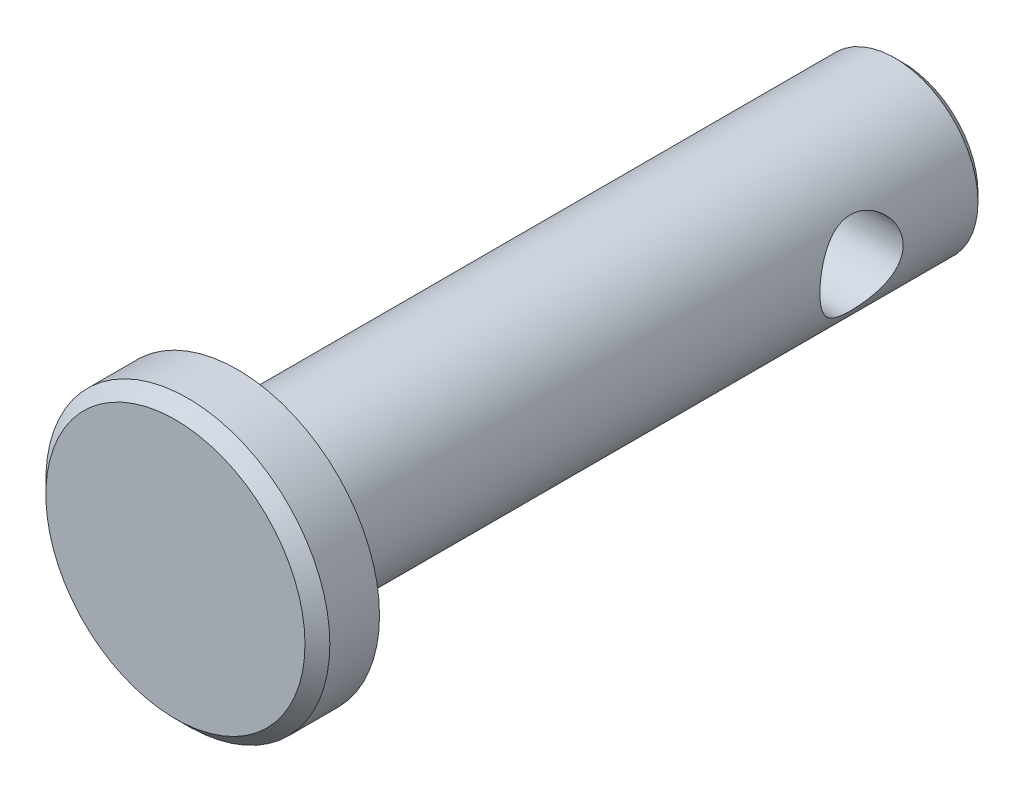
SolidWorks part; units mm, degrees
ref_plane "Front" through (0, 0, 0) normal (0, 0, 1) x (1, 0, 0)
ref_plane "Top" through (0, 0, 0) normal (0, 1, 0) x (1, 0, 0)
ref_plane "Right" through (0, 0, 0) normal (1, 0, 0) x (0, 0, -1)
sketch "Sketch1" plane through (0, 0, 0) normal (0, 0, 1) x (1, 0, 0)
  circle A0 centre (0, 0) radius 2.3812
  point P3 (0, 2.3812)
  point P4 (0, -2.3812)
  dimension "dia" = 4.7625
extrude "Extrude1" add sketch "Sketch1" along normal mid plane 19.05
sketch "Sketch2" plane through (0, 0, 9.525) normal (0, 0, 1) x (1, 0, 0)
  circle A0 centre (0, 0) radius 4.064
  dimension "head dia" = 8.128
extrude "Extrude2" add sketch "Sketch2" along normal blind 1.778
chamfer "Chamfer1" distance 0.3556 angle 45 1 edges at (4.064, 0, 11.303)
sketch "Sketch3" plane through (0, 0, 0) normal (1, 0, 0) x (0, 0, -1)
  line L0 (-9.525, -2.3812) -> (-9.525, 2.3812) construction
  circle A0 centre (5.9531, 0) radius 1.1906
  point P2 (4.7625, 0)
  dimension "hole dia" = 2.3813
  dimension "useable Lg" = 14.2875
extrude "Extrude3" cut sketch "Sketch3" against normal through all and the other way through all
chamfer "Chamfer2" distance 0.2381 angle 45 1 edges at (2.3812, 0, -9.525)
ref_plane "Plane1" through (0, 0, -5.9531) normal (0, 0, 1) x (1, 0, 0)
sketch "Sketch8" plane through (0, 0, 0) normal (1, 0, 0) x (0, 0, -1)
  line L0 (-11.303, 3.7084) -> (-11.303, -3.7084) construction
  line L1 (-10.9474, -4.064) -> (-9.525, -4.064) construction
  line L2 (9.525, -2.1431) -> (9.525, 2.1431) construction
  point P0 (-11.303, 4.064)
  point P1 (-9.525, 4.064)
  point P5 (9.525, 2.3812)
  point P8 (-11.303, -4.064)
  point P9 (9.525, -2.3812)
equation "\"D1@Chamfer1\" = \"head ht@Extrude2\" * .2"
equation "\"D1@Chamfer2\" = \"dia@Sketch1\" * .05"
